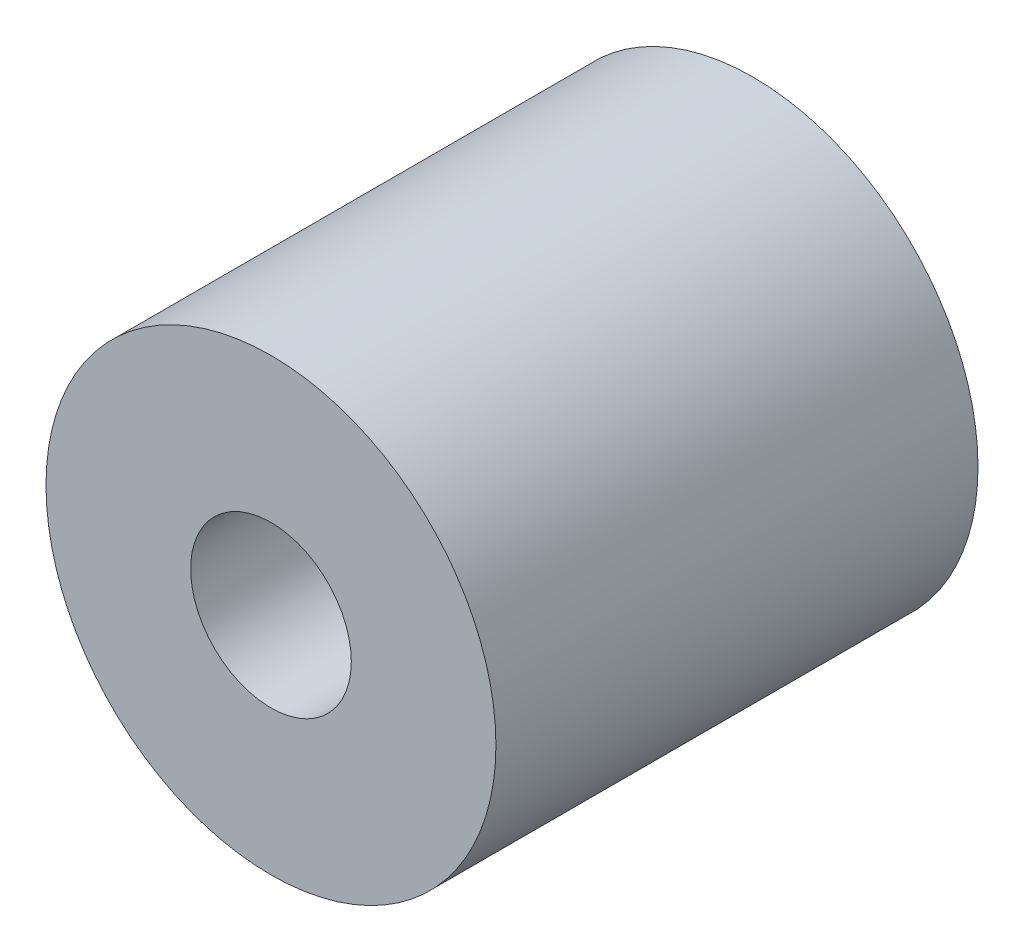
SolidWorks part; units mm, degrees
ref_plane "前视基准面" through (0, 0, 0) normal (0, 0, 1) x (1, 0, 0)
ref_plane "上视基准面" through (0, 0, 0) normal (0, 1, 0) x (1, 0, 0)
ref_plane "右视基准面" through (0, 0, 0) normal (1, 0, 0) x (0, 0, -1)
other "Configuration Table"
sketch "草图1" plane through (0, 0, 0) normal (0, 0, 1) x (1, 0, 0)
  circle A0 centre (0, 0) radius 7
  dimension "diameter" = 14
extrude "Factory_insert" add sketch "草图1" along normal blind 15
sketch "草图2" plane through (0, 0, 15) normal (0, 0, 1) x (1, 0, 0)
  circle A0 centre (0, 0) radius 2.5
  dimension "diameter" = 5
extrude "Thread_envelope" cut sketch "草图2" against normal through all
